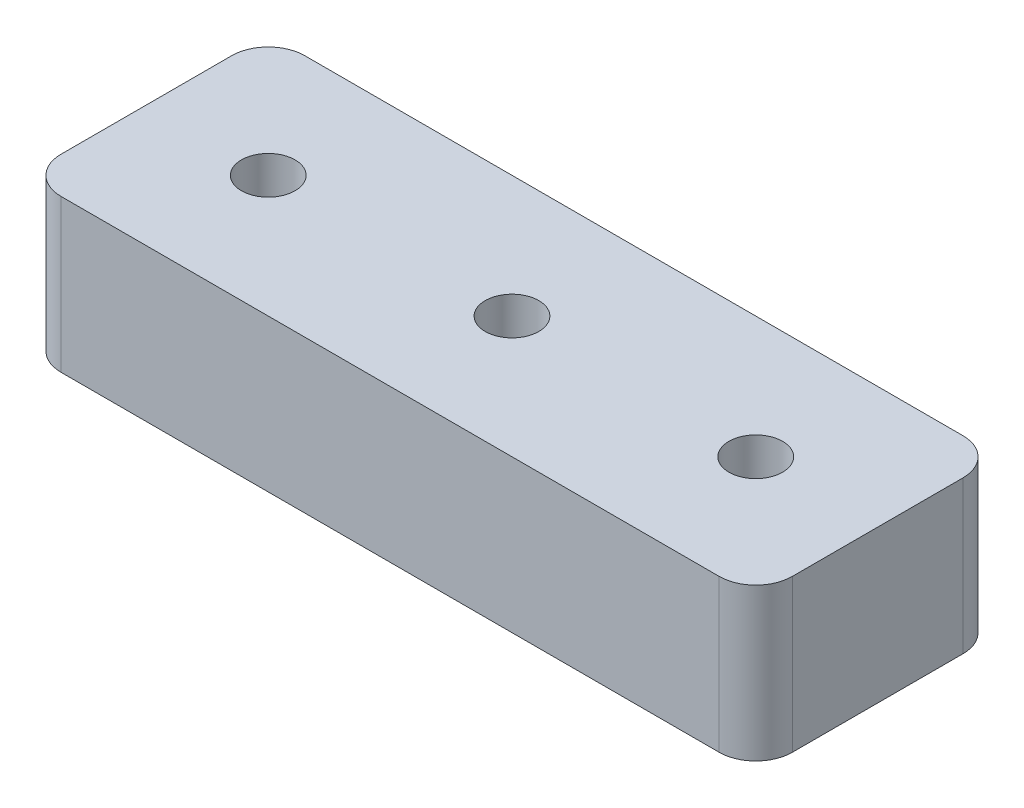
SolidWorks part; units mm, degrees
ref_plane "前视基准面" through (0, 0, 0) normal (0, 0, 1) x (1, 0, 0)
ref_plane "上视基准面" through (0, 0, 0) normal (0, 1, 0) x (1, 0, 0)
ref_plane "右视基准面" through (0, 0, 0) normal (1, 0, 0) x (0, 0, -1)
other "Configuration Table"
sketch "草图1" plane through (0, 0, 0) normal (0, 1, 0) x (1, 0, 0)
  line L0 (0, 0) -> (-20, 0) construction
  line L1 (-30, 10) -> (30, 10)
  line L2 (-30, 10) -> (-30, -10)
  line L3 (-30, -10) -> (30, -10)
  line L4 (30, 10) -> (30, -10)
  line L5 (-30, 10) -> (30, -10) construction
  line L6 (-30, -10) -> (30, 10) construction
  line L7 (0, 7.3749) -> (0, -7.0295) construction
  circle A0 centre (0, 0) radius 2.2
  circle A1 centre (-20, 0) radius 2.2
  circle A2 centre (20, 0) radius 2.2
  point P0 (0, 0)
  dimension "D3" = 4.4
  dimension "D4" = 20
  dimension "D1" = 20
  dimension "D2" = 60
extrude "凸台-拉伸1" add sketch "草图1" along normal mid plane 12.5
fillet "圆角1" radius 3 4 edges at (30, 0, -10) (30, 0, 10) (-30, 0, 10) (-30, 0, -10)
